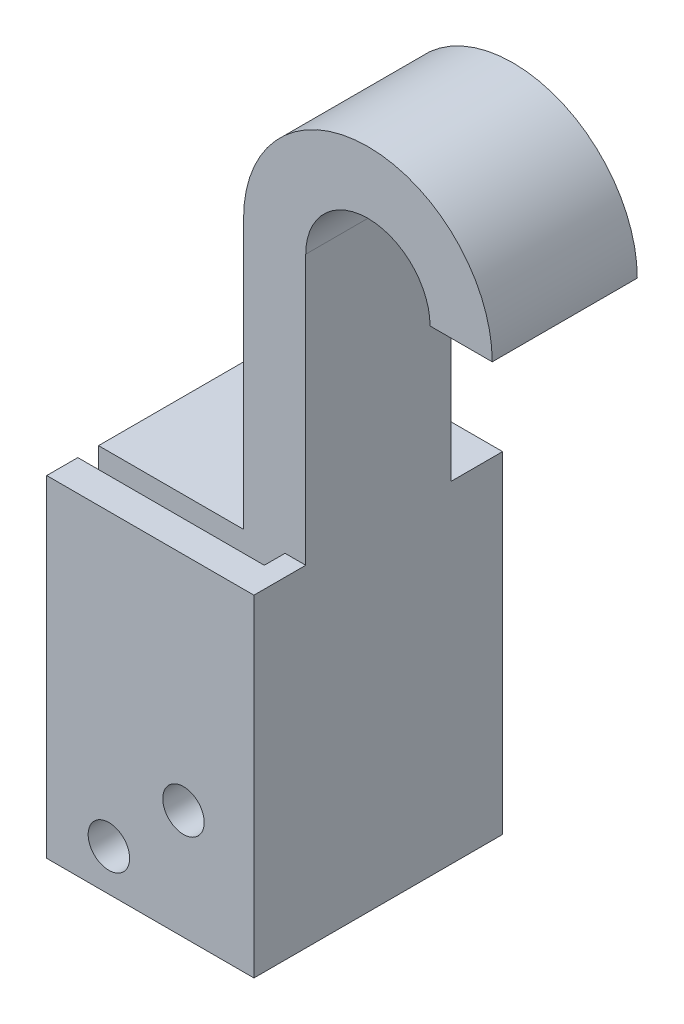
SolidWorks part; units mm, degrees
ref_plane "Front Plane" through (0, 0, 0) normal (0, 0, 1) x (1, 0, 0)
ref_plane "Top Plane" through (0, 0, 0) normal (0, 1, 0) x (1, 0, 0)
ref_plane "Right Plane" through (0, 0, 0) normal (1, 0, 0) x (0, 0, -1)
sketch "Sketch1" plane through (0, 0, 0) normal (0, 0, 1) x (1, 0, 0)
  line L0 (0, 0) -> (-25.4, 0)
  line L1 (0, 0) -> (0, 152.4)
  line L2 (-25.4, 0) -> (-25.4, 152.4)
  line L3 (0, 152.4) -> (-25.4, 152.4)
  line L4 (-25.4, 0) -> (-25.4, 25.4)
  line L5 (-25.4, 0) -> (-25.654, 0)
  line L6 (-25.4, 25.4) -> (-25.654, 25.4)
  line L7 (-25.654, 0) -> (-25.654, 25.4)
  line L8 (-25.4, 177.8) -> (-25.4, -25.4)
  line L9 (-25.4, 177.8) -> (25.4, 177.8)
  line L10 (-25.4, -25.4) -> (25.4, -25.4)
  line L11 (25.4, 177.8) -> (25.4, -25.4)
  dimension "D1" = 25.4
  dimension "D2" = 152.4
  dimension "D3" = 25.4
  dimension "D4" = 0.254
  dimension "D5" = 50.8
  dimension "D6" = 25.4
  dimension "D7" = 25.4
extrude "Boss-Extrude1" add sketch "Sketch1" along normal mid plane 152.4 contours L7 L5 L2 L6 | L1 L3 L2 L0 | L11 L9 L8 L3 L1 L0 L10
sketch "Sketch5" plane through (0, 0, 0) normal (0, 0, 1) x (1, 0, 0)
  line L0 (25.4, -25.4) -> (63.5, -25.4)
  line L1 (25.4, -25.4) -> (25.4, 342.9)
  line L2 (63.5, -25.4) -> (63.5, 342.9)
  line L3 (25.4, 342.9) -> (63.5, 342.9)
  line L4 (25.4, 342.9) -> (63.5, 342.9)
  line L5 (139.7, 342.9) -> (177.8, 342.9)
  line L6 (25.4, 342.9) -> (63.5, 342.9)
  arc A0 (177.8, 342.9) -> (25.4, 342.9) centre (101.6, 342.9) ccw
  arc A1 (139.7, 342.9) -> (63.5, 342.9) centre (101.6, 342.9) ccw
  dimension "D3" = 152.4
  dimension "D1" = 368.3
  dimension "D2" = 38.1
extrude "Boss-Extrude2" add sketch "Sketch5" along normal mid plane 88.9 contours A1 L5 A0 L3 | L3 L1 L0 L2
sketch "Sketch3" plane through (0, 177.8, 0) normal (0, 1, 0) x (1, 0, 0)
  line L0 (-25.4, -76.2) -> (-25.4, -50.8)
  line L4 (-25.4, -76.2) -> (-25.4, 76.2) construction
  line L5 (-25.4, -50.8) -> (25.4, -50.8)
  line L6 (25.4, -44.45) -> (25.4, 44.45) construction
  dimension "D1" = 25.4
ref_plane "Plane1" through (0, 0, 50.8) normal (0, 0, 1) x (1, 0, 0)
sketch "Sketch6" plane through (0, 0, 0) normal (0, 0, 1) x (1, 0, 0)
  line L1 (-63.5, 177.8) -> (63.5, 177.8)
  line L2 (-63.5, 177.8) -> (-63.5, -25.4)
  line L3 (-63.5, -25.4) -> (63.5, -25.4)
  line L4 (63.5, 177.8) -> (63.5, -25.4)
  dimension "D1" = 127
extrude "Boss-Extrude3" add sketch "Sketch6" along normal mid plane 152.4
sketch "Sketch7" plane through (0, 0, 0) normal (0, 0, 1) x (1, 0, 0)
  circle A0 centre (-25.4, 0) radius 12.7
  circle A1 centre (20.32, 41.91) radius 12.7
  point P2 (0, 0)
  point P3 (0, 0)
  point P4 (0, 0)
  point P6 (0, 0)
  dimension "D1" = 25.4
  dimension "D5" = 25.4
  dimension "D3" = 41.91
  dimension "D4" = 45.72
extrude "Cut-Extrude1" cut sketch "Sketch7" against normal through all both and the other way through all
sketch "Sketch8" plane through (0, 0, 50.8) normal (0, 0, 1) x (1, 0, 0)
  line L0 (63.5, -25.4) -> (63.5, 177.8) construction
  line L1 (50.8, -12.7) -> (-63.5, -12.7)
  line L2 (50.8, -12.7) -> (50.8, 177.8)
  line L3 (50.8, 177.8) -> (-63.5, 177.8)
  line L4 (-63.5, -12.7) -> (-63.5, 177.8)
  line L5 (-63.5, -25.4) -> (63.5, -25.4) construction
  point P6 (0, 0)
  dimension "D1" = 12.7
  dimension "D2" = 12.7
extrude "Cut-Extrude2" cut sketch "Sketch8" against normal mid plane 12.7
mirror "Mirror1" about plane through (0, 0, 0) normal (0, 0, 1) of "Cut-Extrude2"
